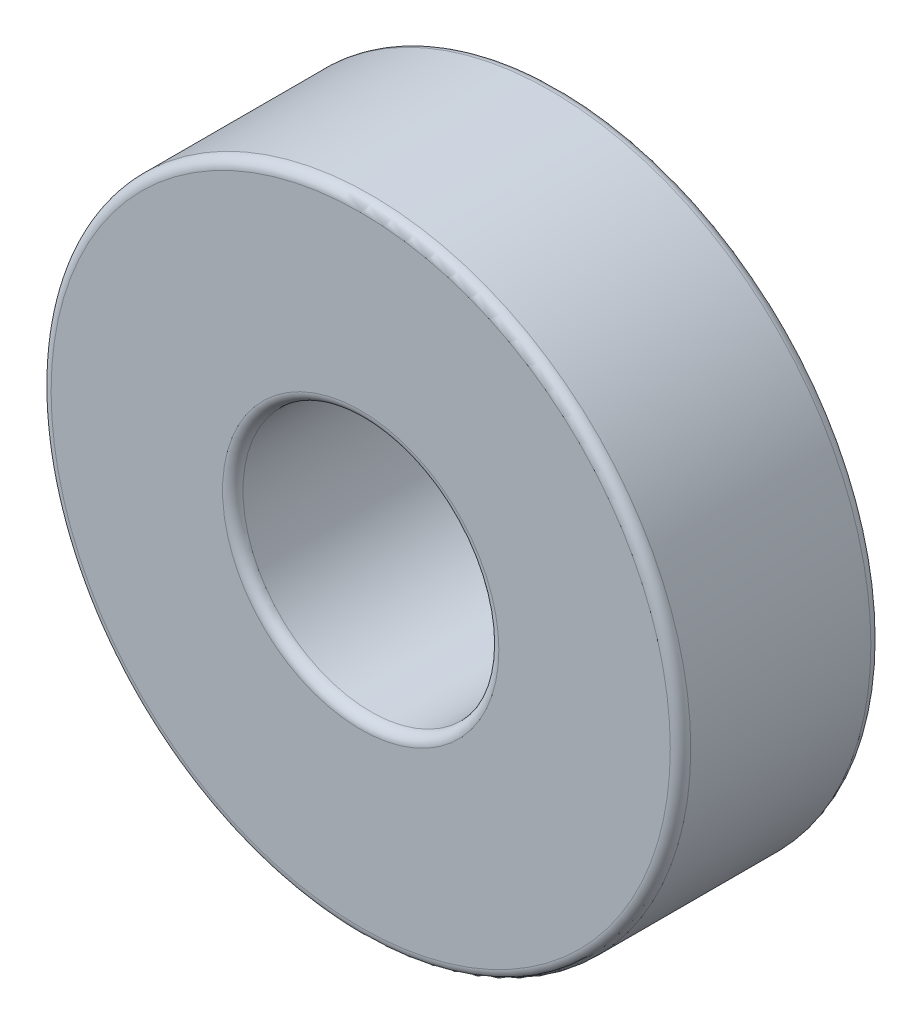
SolidWorks part; units mm, degrees
ref_plane "Front Plane" through (0, 0, 0) normal (0, 0, 1) x (1, 0, 0)
ref_plane "Top Plane" through (0, 0, 0) normal (0, 1, 0) x (1, 0, 0)
ref_plane "Right Plane" through (0, 0, 0) normal (1, 0, 0) x (0, 0, -1)
sketch "Sketch1" plane through (0, 0, 0) normal (0, 0, 1) x (1, 0, 0)
  circle A0 centre (0, 0) radius 7.9375
  dimension "D1" = 15.875
extrude "Boss-Extrude1" add sketch "Sketch1" against normal blind 4.9784
sketch "Sketch2" plane through (0, 0, 0) normal (0, 0, 1) x (1, 0, 0)
  circle A0 centre (0, 0) radius 3.175
  dimension "D1" = 6.35
extrude "Cut-Extrude1" cut sketch "Sketch2" against normal through all both and the other way through all
fillet "Fillet1" radius 0.254 1 edges at (7.9375, 0, 0)
fillet "Fillet2" radius 0.254 3 edges at (3.175, 0, 0) (3.175, 0, -4.9784) (7.9375, 0, -4.9784)
